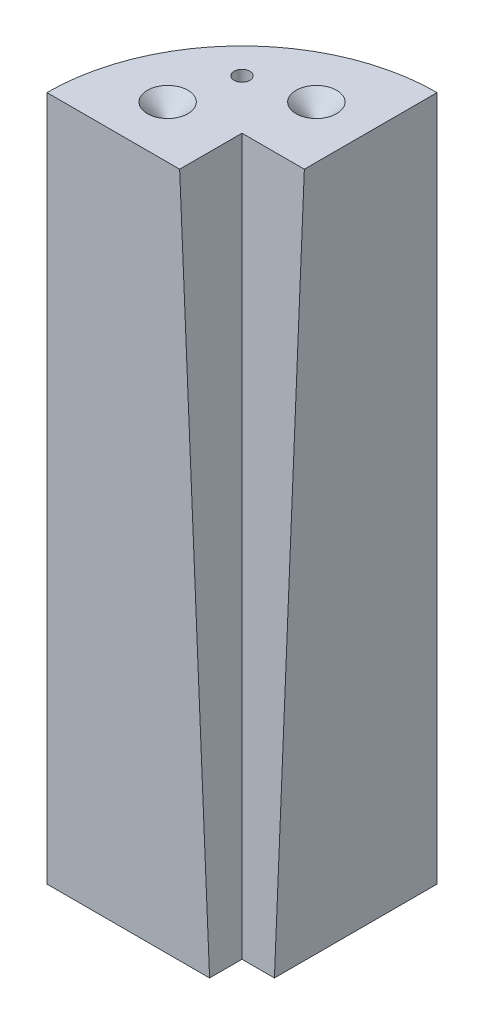
SolidWorks part; units mm, degrees
ref_plane "Front Plane" through (0, 0, 0) normal (0, 0, 1) x (1, 0, 0)
ref_plane "Top Plane" through (0, 0, 0) normal (0, 1, 0) x (1, 0, 0)
ref_plane "Right Plane" through (0, 0, 0) normal (1, 0, 0) x (0, 0, -1)
sketch "Sketch1" plane through (0, 0, 0) normal (0, 1, 0) x (1, 0, 0)
  circle A0 centre (0, 0) radius 46.99
  dimension "D1" = 93.98
extrude "Boss-Extrude1" add sketch "Sketch1" along normal blind 330.2
sketch "Sketch2" plane through (0, 330.2, 0) normal (0, 1, 0) x (1, 0, 0)
  line L0 (-46.99, 0) -> (46.99, 0) construction
  line L1 (0, 46.99) -> (0, -46.99) construction
  line L3 (-22.225, 22.225) -> (22.225, 22.225)
  line L4 (-22.225, 22.225) -> (-22.225, -22.225)
  line L5 (-22.225, -22.225) -> (22.225, -22.225)
  line L6 (22.225, 22.225) -> (22.225, -22.225)
  circle A0 centre (0, 0) radius 46.99 construction
  dimension "D1" = 44.45
  dimension "D2" = 44.45
  dimension "D3" = 22.225
  dimension "D4" = 22.225
extrude "Cut-Extrude1" cut sketch "Sketch2" against normal blind 330.2 draft 2.5
sketch "Sketch3" plane through (0, 330.2, 0) normal (0, 1, 0) x (1, 0, 0)
  line L2 (0, 12.7) -> (0, 46.99)
  line L3 (-12.7, 0) -> (-46.99, 0)
  line L6 (0, 12.7) -> (0, 0)
  line L7 (0, 0) -> (-12.7, 0)
  line L8 (-22.225, 22.225) -> (-22.225, -22.225) construction
  line L9 (22.225, 22.225) -> (-22.225, 22.225) construction
  arc A0 (-46.99, 0) -> (0, 46.99) centre (0, 0) ccw
  circle A1 centre (0, 0) radius 46.99 construction
  circle A3 centre (-26.9875, 26.9875) radius 1.905
  dimension "D1" = 3.81
  dimension "D2" = 4.7625
  dimension "D3" = 4.7625
extrude "Cut-Extrude2" cut sketch "Sketch3" against normal blind 330.2
sketch "Sketch7" plane through (0, 330.2, 0) normal (0, 1, 0) x (1, 0, 0)
  line L0 (0, 46.99) -> (0, 0)
  line L1 (0, 0) -> (-46.99, 0)
  arc A0 (0, 46.99) -> (-46.99, 0) centre (0, 0) ccw
extrude "Cut-Extrude4" cut sketch "Sketch7" against normal blind 165.1
sketch "Sketch8" plane through (0, 165.1, 0) normal (0, 1, 0) x (1, 0, 0)
  circle A0 centre (-12.573, 30.48) radius 4.8895
  circle A1 centre (-30.48, 12.573) radius 4.8895
  dimension "D1" = 9.779
  dimension "D2" = 9.779
  dimension "D3" = 30.48
  dimension "D4" = 12.573
  dimension "D5" = 30.48
  dimension "D6" = 12.573
extrude "Cut-Extrude5" cut sketch "Sketch8" against normal blind 4.7879 draft 45
